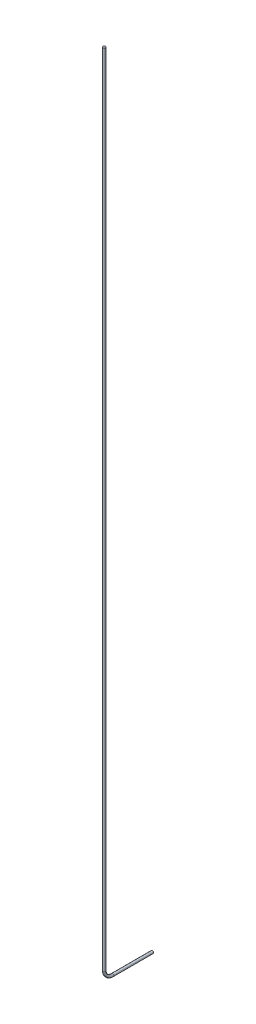
SolidWorks part; units mm, degrees
ref_plane "正面" through (0, 0, 0) normal (0, 0, 1) x (1, 0, 0)
ref_plane "平面" through (0, 0, 0) normal (0, 1, 0) x (1, 0, 0)
ref_plane "右側面" through (0, 0, 0) normal (1, 0, 0) x (0, 0, -1)
sketch "ｽｹｯﾁ1" plane through (0, 0, 0) normal (0, 0, 1) x (1, 0, 0)
  circle A0 centre (0, 0) radius 0.8
  dimension "D1" = 1.6
extrude "ﾎﾞｽ - 押し出し1" add sketch "ｽｹｯﾁ1" along normal blind 20
sketch "ｽｹｯﾁ2" plane through (0, 0, 20) normal (0, 0, 1) x (1, 0, 0)
  circle A1 centre (0, 0) radius 0.8
  circle A2 centre (0, 0) radius 0.8
  dimension "D1" = 0
sketch "ｽｹｯﾁ3" plane through (0, 0, 0) normal (1, 0, 0) x (0, 0, -1)
  line L0 (-20, 0) -> (-25, 0)
  line L1 (-20, 0.8) -> (-20, -0.8) construction
  line L2 (-30, 5) -> (-30, 505)
  line L3 (-20, 0.8) -> (-20, -0.8) construction
  arc A0 (-25, 0) -> (-30, 5) centre (-25, 5) cw
  point P8 (-30, 0)
  dimension "D2" = 5
  dimension "D1" = 10
  dimension "D3" = 500
sweep "ｽｲｰﾌﾟ1" add profiles "ｽｹｯﾁ2" path "ｽｹｯﾁ3"
